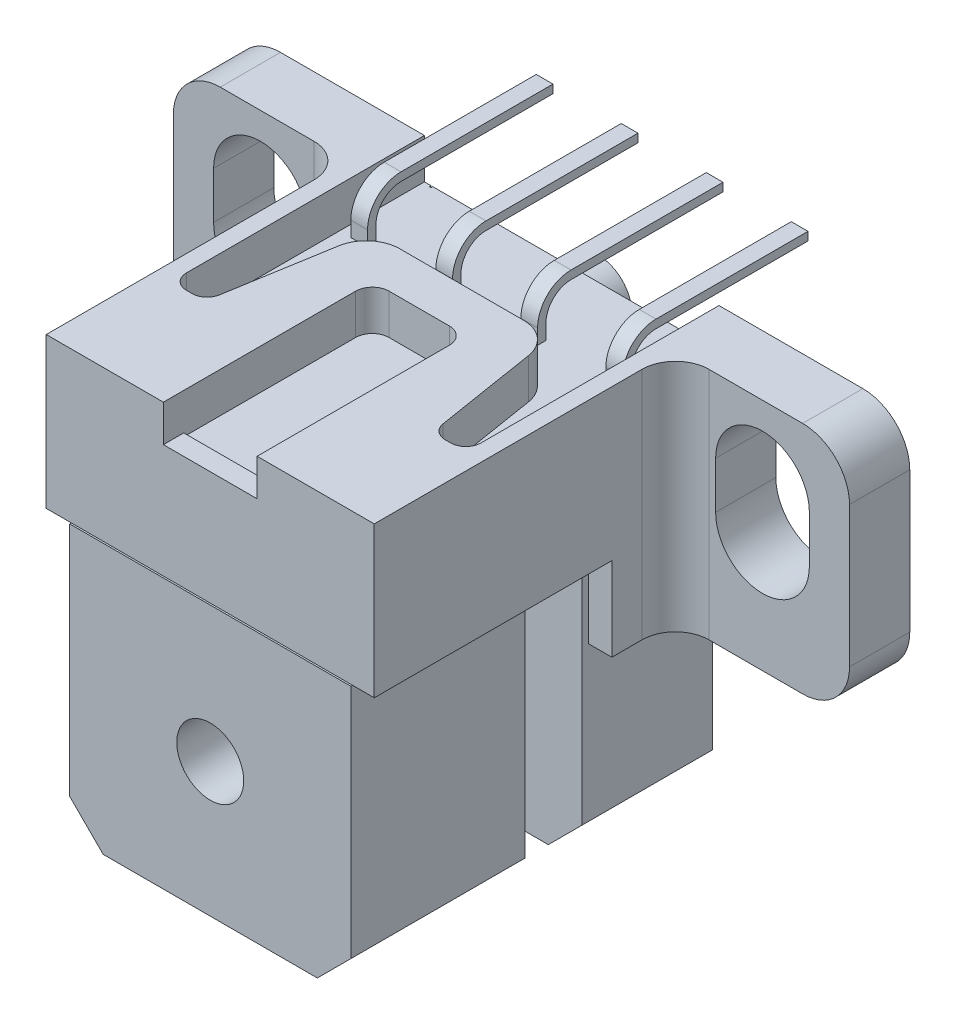
SolidWorks part; units mm, degrees
ref_plane "Спереди" through (0, 0, 0) normal (0, 0, 1) x (1, 0, 0)
ref_plane "Сверху" through (0, 0, 0) normal (0, 1, 0) x (1, 0, 0)
ref_plane "Справа" through (0, 0, 0) normal (1, 0, 0) x (0, 0, -1)
sketch "Эскиз1" plane through (0, 0, 0) normal (0, 0, 1) x (1, 0, 0)
  line L0 (7.4, 0) -> (8.4, 1)
  line L1 (1, 0) -> (7.4, 0)
  line L2 (0, 1) -> (0, 12.6)
  line L3 (0, 12.6) -> (8.4, 12.6)
  line L4 (8.4, 1) -> (8.4, 12.6)
  line L5 (0, 1) -> (1, 0)
  point P0 (0, 0)
  point P3 (8.4, 0)
  dimension "D1" = 12.6
  dimension "D2" = 8.4
extrude "Бобышка-Вытянуть1" add sketch "Эскиз1" along normal blind 10.8
sketch "Эскиз2" plane through (0, 0, 0) normal (0, 0, -1) x (-1, 0, 0)
  line L0 (-8.4, 12.6) -> (0, 12.6) construction
  circle A0 centre (-4.2, 10.3) radius 1
  circle A1 centre (-4.2, 3.9) radius 1
  dimension "D2" = 6.4
  dimension "D3" = 2
  dimension "D1" = 8.7
extrude "Бобышка-Вытянуть2" add sketch "Эскиз2" along normal blind 0.8
sketch "Эскиз3" plane through (8.4, 0, 0) normal (1, 0, 0) x (0, 0, -1)
  line L0 (-10.8, 0) -> (0, 0) construction
  line L1 (-3.9, 0) -> (-5.6, 0)
  line L2 (-3.9, 0) -> (-3.9, 8.1)
  line L3 (-3.9, 8.1) -> (-5.6, 8.1)
  line L4 (-5.6, 0) -> (-5.6, 8.1)
  line L5 (0, 12.6) -> (0, 1) construction
  line L6 (0.8, 2.9) -> (0.8, 4.9) construction
  line L7 (0.8, 3.9) -> (-1.4983, 3.9) construction
  dimension "D1" = 3.9
  dimension "D2" = 1.7
  dimension "D3" = 4.2
extrude "Вырез-Вытянуть1" cut sketch "Эскиз3" against normal blind 17.8
sketch "Эскиз4" plane through (0, 12.6, 0) normal (0, 1, 0) x (1, 0, 0)
  line L0 (9.1, -10.8) -> (-0.7, -10.8)
  line L1 (14.3, 0) -> (-5.9, 0)
  line L3 (8.4, 0) -> (0, 0) construction
  line L4 (14.3, 0) -> (14.3, -1.8)
  line L5 (14.3, -1.8) -> (10.1, -1.8)
  line L6 (9.1, -2.8) -> (9.1, -10.8)
  line L7 (-0.7, -10.8) -> (-0.7, -2.8)
  line L8 (-1.7, -1.8) -> (-5.9, -1.8)
  line L9 (-5.9, -1.8) -> (-5.9, 0)
  arc A0 (-0.7, -2.8) -> (-1.7, -1.8) centre (-1.7, -2.8) ccw
  arc A1 (10.1, -1.8) -> (9.1, -2.8) centre (10.1, -2.8) ccw
  point P5 (4.2, -10.8)
  point P9 (4.2, 0)
  dimension "D5" = 1
  dimension "D1" = 9.8
  dimension "D2" = 20.2
  dimension "D3" = 1.8
  dimension "D4" = 1.8
extrude "Бобышка-Вытянуть3" add sketch "Эскиз4" against normal up to vertex
sketch "Эскиз5" plane through (0, 0, 10.8) normal (0, 0, 1) x (1, 0, 0)
  line L0 (0, 8.1) -> (0, 1) construction
  line L1 (8.4, 8.1) -> (0, 8.1)
  line L2 (8.4, 8.1) -> (8.4, 8.05)
  line L3 (8.4, 8.05) -> (0, 8.05)
  line L4 (0, 8.1) -> (0, 8.05)
extrude "Вырез-Вытянуть2" cut sketch "Эскиз5" against normal blind 1
sketch "Эскиз6" plane through (0, 0, 10.8) normal (0, 0, 1) x (1, 0, 0)
  line L0 (1, 0) -> (7.4, 0) construction
  circle A0 centre (4.2, 4) radius 1
  dimension "D1" = 4
  dimension "D2" = 2
extrude "Вырез-Вытянуть3" cut sketch "Эскиз6" against normal blind 8
sketch "Эскиз7" plane through (0, 12.6, 0) normal (0, 1, 0) x (1, 0, 0)
  line L0 (8.6, 0) -> (8.6, -7.1124)
  line L1 (14.3, 0) -> (-5.9, 0) construction
  line L2 (8.15, -7.5624) -> (7.9834, -7.5624)
  line L3 (7.5391, -7.1839) -> (7.0497, -4.1412)
  line L4 (6.0624, -3.3) -> (2.3617, -3.3)
  line L5 (1.3755, -4.1344) -> (0.863, -7.1869)
  line L6 (0.4192, -7.5624) -> (0.25, -7.5624)
  line L7 (-0.2, -7.1124) -> (-0.2, 0)
  line L8 (9.1, -10.8) -> (9.1, -2.8) construction
  line L9 (-0.7, -2.8) -> (-0.7, -10.8) construction
  line L10 (8.6, 0) -> (-0.2, 0)
  line L11 (4.2, -10.8) -> (5.6, -10.8)
  line L12 (9.1, -10.8) -> (-0.7, -10.8) construction
  line L13 (5.6, -10.8) -> (5.6, -5.0564)
  line L14 (5.1, -4.5564) -> (3.3, -4.5564)
  line L15 (2.8, -5.0564) -> (2.8, -10.8)
  line L16 (2.8, -10.8) -> (4.2, -10.8)
  arc A0 (2.3617, -3.3) -> (1.3755, -4.1344) centre (2.3617, -4.3) ccw
  arc A1 (7.0497, -4.1412) -> (6.0624, -3.3) centre (6.0624, -4.3) ccw
  arc A2 (0.25, -7.5624) -> (-0.2, -7.1124) centre (0.25, -7.1124) cw
  arc A3 (0.863, -7.1869) -> (0.4192, -7.5624) centre (0.4192, -7.1124) cw
  arc A4 (7.9834, -7.5624) -> (7.5391, -7.1839) centre (7.9834, -7.1124) cw
  arc A5 (8.6, -7.1124) -> (8.15, -7.5624) centre (8.15, -7.1124) cw
  arc A6 (3.3, -4.5564) -> (2.8, -5.0564) centre (3.3, -5.0564) ccw
  arc A7 (5.6, -5.0564) -> (5.1, -4.5564) centre (5.1, -5.0564) ccw
  point P23 (-0.2, -7.5624)
  point P26 (0.8, -7.5624)
  point P29 (7.6, -7.5624)
  point P32 (8.6, -7.5624)
  dimension "D6" = 1
  dimension "D7" = 0.45
  dimension "D8" = 0.5
  dimension "D1" = 0.5
  dimension "D2" = 0.5
  dimension "D3" = 1
  dimension "D4" = 1
  dimension "D5" = 3.3
extrude "Вырез-Вытянуть4" cut sketch "Эскиз7" against normal blind 1.2
sketch "Эскиз8" plane through (0, 11.4, 0) normal (0, 1, 0) x (1, 0, 0)
  line L0 (2.8, -5.0564) -> (2.8, -10.8) construction
  line L1 (5.6, -10.8) -> (2.8, -10.8)
  line L2 (5.6, -10.8) -> (5.6, -10.1916)
  line L3 (5.6, -10.1916) -> (2.8, -10.1916)
  line L4 (2.8, -10.8) -> (2.8, -10.1916)
extrude "Бобышка-Вытянуть4" add sketch "Эскиз8" along normal blind 0.1
sketch "Эскиз9" plane through (0, 8.1, 0) normal (0, -1, 0) x (1, 0, 0)
  line L0 (0, 0) -> (0, 3.7)
  line L1 (0, 0) -> (0, 3.9) construction
  line L2 (0, 3.7) -> (-0.7, 3.7)
  line L3 (-0.7, 2.8) -> (-0.7, 10.8) construction
  line L4 (-0.7, 3.7) -> (-0.7, 2.8)
  line L5 (-1.7, 1.8) -> (-5.9, 1.8)
  line L6 (-5.9, 1.8) -> (-5.9, 0)
  line L7 (-5.9, 0) -> (0, 0)
  line L8 (14.3, 0) -> (8.4, 0)
  line L9 (8.4, 0) -> (8.4, 3.7)
  line L10 (8.4, 3.9) -> (8.4, 0) construction
  line L11 (8.4, 3.7) -> (9.1, 3.7)
  line L12 (9.1, 10.8) -> (9.1, 2.8) construction
  line L13 (9.1, 3.7) -> (9.1, 2.8)
  line L14 (1, 3.9) -> (0, 3.9) construction
  line L15 (10.1, 1.8) -> (14.3, 1.8)
  line L16 (14.3, 1.8) -> (14.3, 0)
  line L17 (0, 3.9) -> (8.4, 3.9) construction
  arc A0 (9.1, 2.8) -> (10.1, 1.8) centre (10.1, 2.8) ccw
  arc A1 (-0.7, 2.8) -> (-1.7, 1.8) centre (-1.7, 2.8) cw
  dimension "D1" = 0.2
  dimension "D2" = 0.2
extrude "Бобышка-Вытянуть5" add sketch "Эскиз9" along normal blind 2.5
sketch "Эскиз10" plane through (0, 8.1, 0) normal (0, -1, 0) x (1, 0, 0)
  line L1 (0, 3.9) -> (8.4, 3.9)
  line L2 (0, 3.9) -> (0, 5.6)
  line L3 (0, 5.6) -> (8.4, 5.6)
  line L4 (8.4, 3.9) -> (8.4, 5.6)
extrude "Вырез-Вытянуть5" cut sketch "Эскиз10" against normal blind 0.05
fillet "Скругление1" radius 1.4 4 edges at (-5.9, 5.6, 0.9) (-5.9, 12.6, 0.9) (14.3, 12.6, 0.9) (14.3, 5.6, 0.9)
sketch "Эскиз11" plane through (0, 0, 0) normal (0, 0, -1) x (-1, 0, 0)
  line L0 (-8.6, 11.4) -> (0.2, 11.4) construction
  line L1 (-8.4, 5.5617) -> (-8.35, 5.5617)
  line L2 (-8.4, 5.5617) -> (-8.4, 11.4)
  line L3 (-8.4, 11.4) -> (-8.35, 11.4)
  line L4 (-8.35, 5.5617) -> (-8.35, 11.4)
  line L6 (0, 5.5712) -> (-0.05, 5.5712)
  line L7 (0, 5.5712) -> (0, 11.4)
  line L8 (0, 11.4) -> (-0.05, 11.4)
  line L9 (-0.05, 5.5712) -> (-0.05, 11.4)
extrude "Вырез-Вытянуть8" cut sketch "Эскиз11" against normal blind 0.05 contours L9 L8 L7 L6 | L4 L3 L2 L1
sketch "Эскиз12" plane through (0, 0, 0) normal (0, 0, -1) x (-1, 0, 0)
  line L0 (3.3, 9) -> (3.3, 10.4) construction
  line L1 (1.9, 9) -> (1.9, 10.4)
  line L2 (4.7, 9) -> (4.7, 10.4)
  line L3 (-11.7, 10.4) -> (-11.7, 9) construction
  line L4 (-10.3, 10.4) -> (-10.3, 9)
  line L5 (-13.1, 10.4) -> (-13.1, 9)
  circle A0 centre (-4.2, 4) radius 1 construction
  arc A1 (-10.3, 10.4) -> (-13.1, 10.4) centre (-11.7, 10.4) ccw
  arc A4 (1.9, 9) -> (4.7, 9) centre (3.3, 9) ccw
  arc A5 (4.7, 10.4) -> (1.9, 10.4) centre (3.3, 10.4) ccw
  arc A6 (-13.1, 9) -> (-10.3, 9) centre (-11.7, 9) ccw
  circle A8 centre (-4.2, 4) radius 1 construction
  point P5 (-11.7, 9.7)
  point P10 (3.3, 9.7)
  dimension "D1" = 7.5
  dimension "D3" = 1.4
  dimension "D5" = 5
  dimension "D2" = 7.5
  dimension "D4" = 1.4
  dimension "D6" = 5
extrude "Вырез-Вытянуть9" cut sketch "Эскиз12" against normal blind 4
sketch "Эскиз13" plane through (0, 11.4, 0) normal (0, 1, 0) x (1, 0, 0)
  line L5 (5.72, -2.54) -> (5.22, -2.54)
  line L6 (5.72, -2.54) -> (5.72, 3)
  line L7 (5.72, 3) -> (5.22, 3)
  line L8 (5.22, -2.54) -> (5.22, 3)
  line L9 (8.26, -2.54) -> (7.76, -2.54)
  line L10 (8.26, -2.54) -> (8.26, 3)
  line L11 (8.26, 3) -> (7.76, 3)
  line L12 (7.76, -2.54) -> (7.76, 3)
  line L13 (3.18, -2.54) -> (2.68, -2.54)
  line L14 (3.18, -2.54) -> (3.18, 3)
  line L15 (3.18, 3) -> (2.68, 3)
  line L16 (2.68, -2.54) -> (2.68, 3)
  line L17 (5.72, -2.54) -> (5.22, -2.54)
  line L18 (5.72, -2.54) -> (5.72, 3)
  line L19 (5.72, 3) -> (5.22, 3)
  line L20 (5.22, -2.54) -> (5.22, 3)
  line L21 (0.64, -2.54) -> (0.14, -2.54)
  line L22 (0.64, -2.54) -> (0.64, 3)
  line L23 (0.64, 3) -> (0.14, 3)
  line L24 (0.14, -2.54) -> (0.14, 3)
extrude "Бобышка-Вытянуть6" add sketch "Эскиз13" along normal blind 1.45 contours L5 L8 L7 L6 | L13 L16 L15 L14 | L21 L24 L23 L22 | L9 L12 L11 L10
fillet "Скругление2" radius 1 4 edges at (0.39, 12.85, 2.54) (2.93, 12.85, 2.54) (5.47, 12.85, 2.54) (8.01, 12.85, 2.54)
sketch "Эскиз14" plane through (0.14, 0, 0) normal (-1, 0, 0) x (0, 0, 1)
  line L0 (-3, 12.6) -> (1.54, 12.6)
  line L1 (-3, 12.85) -> (-3, 11.4) construction
  line L2 (2.29, 11.85) -> (2.29, 11.4)
  line L3 (0, 11.4) -> (7.1124, 11.4) construction
  line L4 (2.29, 11.4) -> (-3, 11.4)
  line L5 (-3, 11.4) -> (-3, 12.6)
  line L6 (1.54, 12.85) -> (-3, 12.85) construction
  line L7 (2.54, 11.85) -> (2.54, 11.4) construction
  arc A0 (1.54, 12.6) -> (2.29, 11.85) centre (1.54, 11.85) cw
  dimension "D3" = 0.75
  dimension "D1" = 0.25
  dimension "D2" = 0.25
extrude "Вырез-Вытянуть10" cut sketch "Эскиз14" against normal up to vertex
